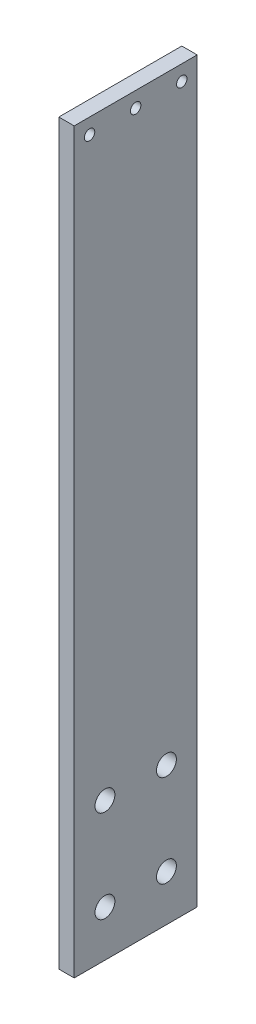
SolidWorks part; units mm, degrees
ref_plane "Front Plane" through (0, 0, 0) normal (0, 0, 1) x (1, 0, 0)
ref_plane "Top Plane" through (0, 0, 0) normal (0, 1, 0) x (1, 0, 0)
ref_plane "Right Plane" through (0, 0, 0) normal (1, 0, 0) x (0, 0, -1)
sketch "Sketch1" plane through (0, 0, 0) normal (1, 0, 0) x (0, 0, -1)
  line L1 (-25.4, 152.4) -> (25.4, 152.4)
  line L2 (-25.4, 152.4) -> (-25.4, -152.4)
  line L3 (-25.4, -152.4) -> (25.4, -152.4)
  line L4 (25.4, 152.4) -> (25.4, -152.4)
  line L5 (-25.4, 152.4) -> (25.4, -152.4) construction
  line L6 (-25.4, -152.4) -> (25.4, 152.4) construction
  point P0 (0, 0)
  dimension "D1" = 50.8
  dimension "D2" = 304.8
extrude "Boss-Extrude1" add sketch "Sketch1" against normal blind 6.35
sketch "Sketch2" plane through (0, 0, 0) normal (1, 0, 0) x (0, 0, -1)
  line L0 (-25.4, 152.4) -> (-25.4, -152.4) construction
  line L2 (25.4, 152.4) -> (-25.4, 152.4) construction
  line L3 (-25.4, -152.4) -> (25.4, -152.4) construction
  circle A0 centre (-12.7, -95.25) radius 4.1021
  circle A1 centre (12.7, -95.25) radius 4.1021
  circle A2 centre (12.7, -133.35) radius 4.1021
  circle A3 centre (-12.7, -133.35) radius 4.1021
  circle A4 centre (-19.05, 146.05) radius 2.1527
  circle A5 centre (0, 146.05) radius 2.1527
  circle A6 centre (19.05, 146.05) radius 2.1527
  dimension "D1" = 8.2042
  dimension "D6" = 4.3053
  dimension "D2" = 12.7
  dimension "D3" = 19.05
  dimension "D7" = 6.35
  dimension "D8" = 6.35
  dimension "D10" = 12.7
  dimension "D11" = 38.1
  dimension "D4" = 2
  dimension "D5" = 2
  dimension "D9" = 3
extrude "Cut-Extrude1" cut sketch "Sketch2" against normal through all
